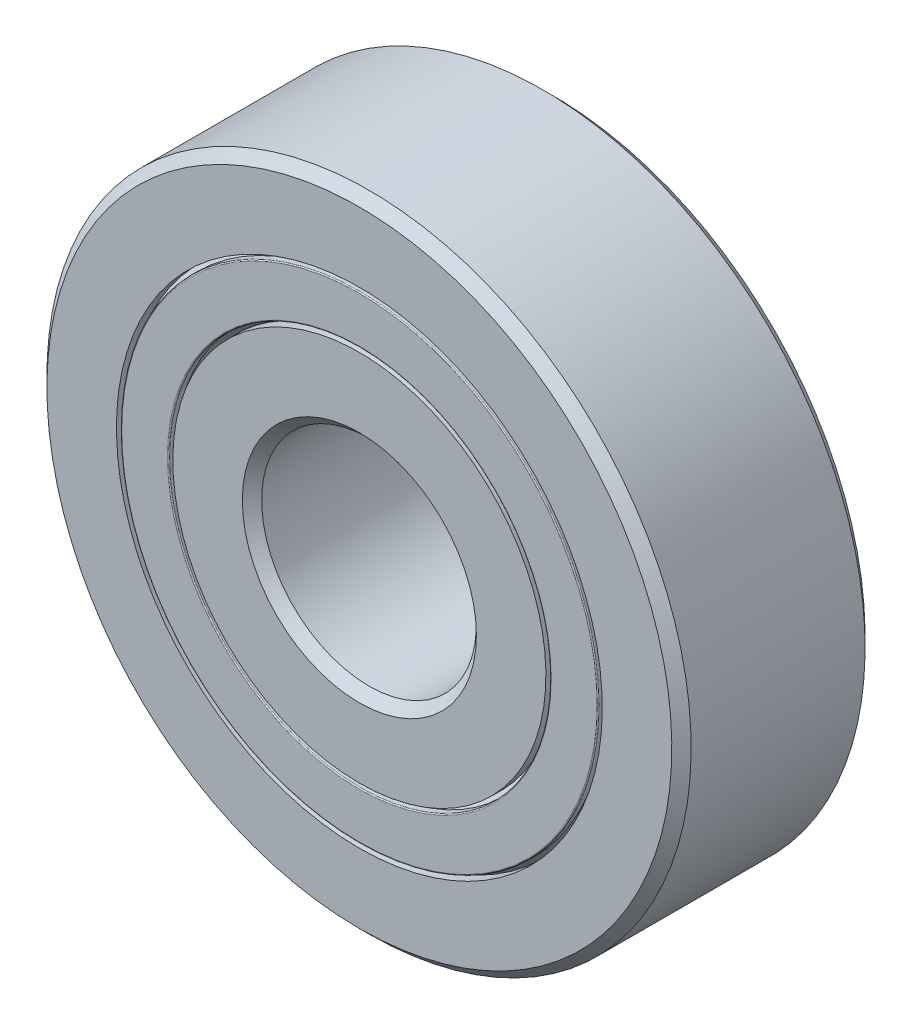
SolidWorks part; units mm, degrees
ref_plane "Front Plane" through (0, 0, 0) normal (0, 0, 1) x (1, 0, 0)
ref_plane "Top Plane" through (0, 0, 0) normal (0, 1, 0) x (1, 0, 0)
ref_plane "Right Plane" through (0, 0, 0) normal (1, 0, 0) x (0, 0, -1)
sketch "Sketch1" plane through (0, 0, 0) normal (0, 0, 1) x (1, 0, 0)
  line L0 (-15, 0) -> (15, 0) construction
  line L1 (-5, 0) -> (5, 0) construction
  circle A0 centre (0, 0) radius 5 construction
  circle A1 centre (0, 0) radius 15 construction
  point P3 (0, 0)
  point P6 (0, 0)
  point P7 (0, -5)
  point P11 (0, -15)
  point P12 (0, 5)
  point P13 (0, 15)
  dimension "OD" = 30
  dimension "ID" = 10
sketch "Sketch2" plane through (0, 0, 0) normal (1, 0, 0) x (0, 0, -1)
  line L0 (-4.5, 15) -> (4.5, 15) construction
  line L1 (0, 15) -> (0, -15) construction
  line L2 (4.05, 15) -> (-4.05, 15)
  line L3 (-4.05, 15) -> (-4.5, 14.55)
  line L4 (-4.5, 14.55) -> (-4.5, 11.3125)
  line L5 (-4.5, 11.3125) -> (-2, 11.3125)
  line L6 (4.5, 11.3125) -> (2, 11.3125)
  line L7 (4.5, 14.55) -> (4.5, 11.3125)
  line L8 (4.05, 15) -> (4.5, 14.55)
  line L9 (0, 15) -> (0, 10) construction
  line L10 (0, 10) -> (0, 5) construction
  line L11 (0, 15) -> (0, -15) construction
  line L12 (-4.5, 0) -> (4.5, 0) construction
  line L13 (4.5, 5) -> (-4.5, 5) construction
  line L14 (0, 12.3922) -> (0, 7.6078) construction
  line L15 (-4.5, -5) -> (4.5, -5) construction
  line L16 (-4.5, 5) -> (-4.5, -5) construction
  line L17 (4.5, 15) -> (4.5, -15) construction
  line L18 (-4.5, 11.3125) -> (-4.5, 11.1813) construction
  line L19 (-4.5, 11.1813) -> (-4.5, 11.05) construction
  line L20 (-4.5, 11.05) -> (-4.5, 10.9187) construction
  line L21 (-4.5, 10.9187) -> (-4.5, 10.7875) construction
  line L22 (-4.5, 10.7875) -> (-4.5, 10.6562) construction
  line L24 (-3.25, 11.3125) -> (-3.25, 10) construction
  arc A0 (-2, 11.3125) -> (2, 11.3125) centre (0, 10) cw
  circle A1 centre (0, 10) radius 2.3922 construction
  point P14 (0, 5)
  point P17 (0, 0)
  point P21 (0, 15)
  point P29 (0, 5)
  point P30 (0, -5)
  point P46 (-3.25, 10.6562)
  dimension "Width" = 9
  dimension "D1" = 45
  dimension "D2" = 0.45
  dimension "D3" = 4
  dimension "D4" = 1.3125
  dimension "For Shaft Diameter" = 10
  dimension "For Housing ID" = 30
sketch "Sketch3" plane through (0, 0, 0) normal (1, 0, 0) x (0, 0, -1)
  line L0 (4.05, 15) -> (4.5, 14.55) construction
  line L1 (4.5, 14.55) -> (4.5, 11.3125) construction
  line L2 (4.5, 11.3125) -> (2, 11.3125) construction
  line L3 (-4.5, 11.3125) -> (-2, 11.3125) construction
  line L4 (-4.5, 14.55) -> (-4.5, 11.3125) construction
  line L5 (-4.05, 15) -> (-4.5, 14.55) construction
  line L6 (4.05, 15) -> (-4.05, 15) construction
  line L7 (4.05, 15) -> (4.5, 14.55)
  line L8 (4.5, 14.55) -> (4.5, 11.3125)
  line L9 (4.5, 11.3125) -> (2, 11.3125)
  line L10 (-4.5, 11.3125) -> (-2, 11.3125)
  line L11 (-4.5, 14.55) -> (-4.5, 11.3125)
  line L12 (-4.05, 15) -> (-4.5, 14.55)
  line L13 (4.05, 15) -> (-4.05, 15)
  arc A0 (2, 11.3125) -> (-2, 11.3125) centre (0, 10) ccw construction
  arc A1 (2, 11.3125) -> (-2, 11.3125) centre (0, 10) ccw
revolve "Revolve1" add sketch "Sketch3" angle 360 about L12
sketch "Sketch4" plane through (0, 0, 0) normal (1, 0, 0) x (0, 0, -1)
  line L0 (0, 15) -> (0, -15) construction
  line L1 (0, 15) -> (0, -15) construction
  line L2 (-4.05, 5) -> (-4.5, 5.45)
  line L3 (-4.5, 5.45) -> (-4.5, 8.6875)
  line L5 (-4.5, 8.6875) -> (-2, 8.6875)
  line L6 (-4.05, 5) -> (4.05, 5)
  line L8 (4.05, 5) -> (4.5, 5.45)
  line L10 (4.5, 5.45) -> (4.5, 8.6875)
  line L11 (4.5, 8.6875) -> (2, 8.6875)
  line L12 (-4.5, 14.55) -> (-4.5, 11.3125) construction
  line L13 (4.05, 15) -> (4.5, 14.55) construction
  line L15 (4.5, -14.55) -> (4.5, 14.55) construction
  line L16 (4.05, 15) -> (4.05, -15) construction
  arc A1 (2, 8.6875) -> (-2, 8.6875) centre (0, 10) cw
  circle A2 centre (0, 10) radius 2.3922 construction
  point P1 (0, 5)
revolve "Revolve2" add sketch "Sketch4" angle 360 about L12
sketch "Sketch5" plane through (0, 0, 0) normal (1, 0, 0) x (0, 0, -1)
  line L0 (-2.3922, 10) -> (2.3922, 10)
  arc A2 (-2.3922, 10) -> (2.3922, 10) centre (0, 10) cw
  arc A3 (2, 11.3125) -> (-2, 11.3125) centre (0, 10) ccw construction
revolve "Revolve3" add sketch "Sketch5" angle 360 about L0
sketch "Sketch6" plane through (0, 0, 0) normal (1, 0, 0) x (0, 0, -1)
  line L0 (-4.5, 11.3125) -> (-4.5, 10.6562) construction
  line L1 (-4.5, 14.55) -> (-4.5, -14.55) construction
  line L2 (-4.5, 10.6562) -> (-4.5, 10) construction
  line L3 (-4.5, 10) -> (-4.5, 9.3437) construction
  line L4 (-4.5, 9.3437) -> (-4.5, 8.6875) construction
  line L5 (-4.5, 10.6562) -> (-4.1334, 10.6562) construction
  line L7 (-2.3004, 10.6562) -> (-2.3004, 9.3438) construction
  line L8 (-4.1334, 10.6562) -> (-3.7668, 10.6562) construction
  line L10 (0, 15) -> (0, -15) construction
  line L11 (0, 15) -> (0, -15) construction
  line L12 (-3.7668, 10.6562) -> (-3.4002, 10.6562) construction
  line L13 (-3.4002, 10.6562) -> (-3.0336, 10.6562) construction
  line L14 (-3.0336, 10.6562) -> (-2.667, 10.6562) construction
  line L15 (-2.667, 10.6562) -> (-2.3004, 10.6562) construction
  line L16 (-2.3004, 10.6562) -> (-2.667, 10.6562)
  line L17 (-2.667, 9.3438) -> (-3.0336, 9.3438) construction
  line L18 (-2.667, 9.3438) -> (-2.3004, 9.3438)
  line L19 (-3.0336, 9.3438) -> (-3.0336, 10.6562) construction
  line L20 (-2.8503, 10.6562) -> (-2.8503, 9.3438) construction
  circle A0 centre (0, 10) radius 2.3922 construction
  circle A1 centre (0, 10) radius 2.3922 construction
  arc A2 (-2.667, 10.6562) -> (-2.667, 9.3438) centre (-1.5839, 10) ccw
  arc A3 (-2.3004, 10.6562) -> (-2.3004, 9.3438) centre (0, 10) ccw
  point P28 (-2.8503, 10)
revolve "Revolve4" add sketch "Sketch6" angle 360 about L11
pattern_circular "CirPattern1" count 8 over 360 about axis through (0, 0, 0) along (0, 0, 1) of bodies 134 104
sketch "Sketch7" plane through (0, 0, 0) normal (0, 0, 1) x (1, 0, 0)
  line L0 (0, 8.6875) -> (0, 9.125) construction
  line L1 (0, 7.6078) -> (0, 12.3922) construction
  line L2 (0, 9.125) -> (0, 9.5625) construction
  line L3 (0, 9.5625) -> (0, 10) construction
  line L4 (0, 10) -> (0, 10.4375) construction
  line L5 (0, 10.4375) -> (0, 10.875) construction
  line L6 (0, 10.875) -> (0, 11.3125) construction
  line L7 (0, 14.55) -> (0, 11.3125) construction
  line L8 (0, 15) -> (0, -15) construction
  circle A0 centre (0, 0) radius 8.6875 construction
  circle A1 centre (0, 0) radius 10
  circle A2 centre (0, 0) radius 10.6562
  point P19 (0, 10.6562)
extrude "Boss-Extrude1" add sketch "Sketch7" along normal mid plane 1.5 separate body
sketch "Sketch8" plane through (0, 0, 0) normal (1, 0, 0) x (0, 0, -1)
  line L0 (-4.5, 11.1813) -> (-4.5, 11.05) construction
  line L1 (-4.5, 11.1156) -> (-4.1667, 11.1156)
  line L2 (-4.5, 11.1156) -> (-4.5, 8.8844)
  line L3 (-4.5, 8.8844) -> (-4.1667, 8.8844)
  line L4 (-4, 11.1156) -> (-4, 8.8844)
  line L5 (0, 15) -> (0, 10) construction
  line L10 (-4.1667, 11.1156) -> (-4, 11.3125)
  line L11 (-4.5, 11.3125) -> (-2, 11.3125) construction
  line L12 (-4, 11.3125) -> (-4, 11.1156)
  line L13 (-4.1667, 8.8844) -> (-4, 8.6875)
  line L14 (-4, 8.6875) -> (-4, 8.8844)
  line L15 (-4.5, 11.3125) -> (-4.3333, 11.3125) construction
  line L16 (4.5, 11.1156) -> (4.5, 8.8844)
  line L17 (4.5, 8.8844) -> (4.1667, 8.8844)
  line L18 (4.1667, 8.8844) -> (4, 8.6875)
  line L19 (4, 8.6875) -> (4, 8.8844)
  line L20 (4, 11.1156) -> (4, 8.8844)
  line L21 (4, 11.3125) -> (4, 11.1156)
  line L22 (4.1667, 11.1156) -> (4, 11.3125)
  line L23 (4.5, 11.1156) -> (4.1667, 11.1156)
  line L24 (-4.3333, 11.3125) -> (-4.1667, 11.3125) construction
  line L25 (-4.1667, 11.3125) -> (-4, 11.3125) construction
  line L27 (-4.5, 8.6875) -> (-2, 8.6875) construction
  point P23 (-4.5, 11.1156)
  dimension "D1" = 0.5
revolve "Revolve5" add sketch "Sketch8" angle 360 about L12
fillet "Fillet1" radius 0.05 2 edges at (0, -11.1156, 4.5) (0, -8.8844, 4.5)
fillet "Fillet2" radius 0.05 2 edges at (0, -8.8844, -4.5) (0, -11.1156, -4.5)
equation "\"D2@Sketch2\" = \"Width@Sketch2\" * .05"
equation "\"D3@Sketch2\" = \"Width@Sketch2\" / 2.25"
equation "\"D4@Sketch2\"=( \"OD@Sketch1\" - \"Width@Sketch2\" )  *.5*.125"
equation "\"D1@Boss-Extrude1\" = \"Width@Sketch2\" / 6"
equation "\"D1@Sketch8\"=(\"Width@Sketch2\"-\"D3@Sketch2\")*.5*.2"
equation "\"D1@Fillet1\"=\"d1@sketch8\"*.1"
equation "\"D1@Fillet2\"=\"d1@fillet1\""
